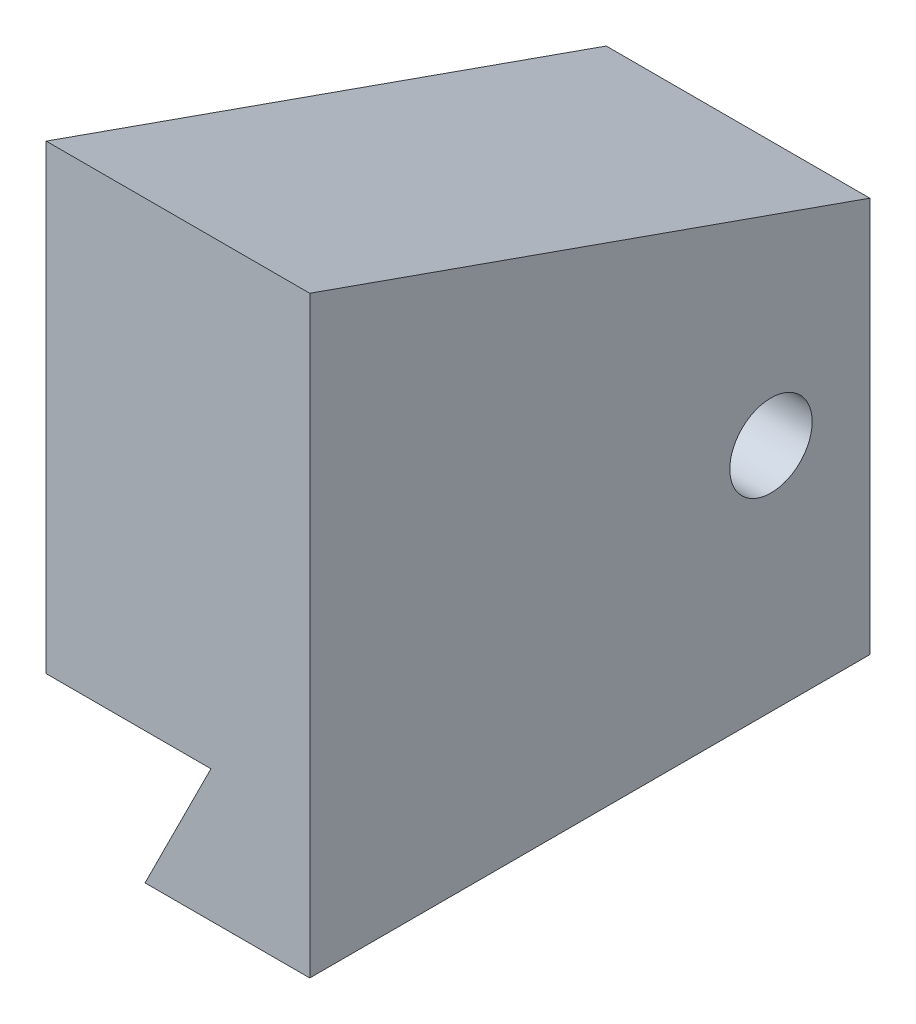
SolidWorks part; units mm, degrees
ref_plane "Front Plane" through (0, 0, 0) normal (0, 0, 1) x (1, 0, 0)
ref_plane "Top Plane" through (0, 0, 0) normal (0, 1, 0) x (1, 0, 0)
ref_plane "Right Plane" through (0, 0, 0) normal (1, 0, 0) x (0, 0, -1)
sketch "Sketch1" plane through (0, 0, 0) normal (1, 0, 0) x (0, 0, -1)
  line L0 (0, 0) -> (0, 12)
  line L1 (0, 12) -> (-17, 18)
  line L2 (-17, 18) -> (-17, 0)
  line L3 (-17, 0) -> (0, 0)
  dimension "D1" = 18
  dimension "D2" = 12
  dimension "D3" = 17
extrude "Boss-Extrude1" add sketch "Sketch1" along normal blind 8
sketch "Sketch2" plane through (8, 0, 0) normal (1, 0, 0) x (0, 0, -1)
  line L0 (-17, 18) -> (-17, 0) construction
  line L1 (-17, 5) -> (0, 5)
  line L2 (-17, 5) -> (-17, 0)
  line L3 (-17, 0) -> (0, 0)
  line L4 (0, 5) -> (0, 0)
  line L5 (0, 0) -> (0, 12) construction
  dimension "D1" = 5
extrude "Cut-Extrude1" [suppressed] cut sketch "Sketch2" against normal blind 4
sketch "Sketch3" plane through (0, 0, 0) normal (0, 0, -1) x (-1, 0, 0)
  line L0 (-8, 0) -> (-5, 0)
  line L1 (-8, 0) -> (0, 0) construction
  line L2 (-5, 0) -> (-3, 4)
  line L3 (-3, 4) -> (-8, 4)
  line L4 (-8, 0) -> (-8, 12) construction
  line L5 (-8, 4) -> (-8, 0)
  dimension "D1" = 5
  dimension "D2" = 3
  dimension "D3" = 4
extrude "Cut-Extrude2" cut sketch "Sketch3" against normal through all
sketch "Sketch5" plane through (8, 0, 0) normal (1, 0, 0) x (0, 0, -1)
  line L0 (0, 4) -> (0, 12) construction
  line L1 (-17, 4) -> (0, 4) construction
  circle A0 centre (-3, 7) radius 1
  dimension "D1" = 2
  dimension "D3" = 3
  dimension "D2" = 3
hole_wizard "M3x0.5 Tapped Hole1" positions "3DSketch1" profile "Sketch6" tap size "M3x0.5" standard "ANSI Metric" end condition through all
sketch3d "3DSketch1"
  point P0 (8, 7, 3)
sketch "Sketch6" plane through (8, 7, 3) normal (0, 1, 0) x (0, 0, -1)
  line L0 (0, 0) -> (0, 16)
  line L1 (0, 16) -> (1.25, 16)
  line L2 (1.25, 16) -> (1.25, 0)
  line L5 (1.25, 0) -> (0, 0)
  line L11 (0, -6.35) -> (0, 107.95) construction
  dimension "Thread Major Dia." = 2.5
  dimension "Thru Tap Drill Depth" = 16
mirror "Mirror1" about plane through (0, 0, 0) normal (1, 0, 0) of "M3x0.5 Tapped Hole1", "Cut-Extrude2", "Boss-Extrude1"
sketch "Sketch7" plane through (8, 0, 0) normal (1, 0, 0) x (0, 0, -1)
  line L1 (-18.597, 19.2943) -> (2.2281, 19.2943)
  line L2 (-18.597, 19.2943) -> (-18.597, -2.2409)
  line L3 (-18.597, -2.2409) -> (2.2281, -2.2409)
  line L4 (2.2281, 19.2943) -> (2.2281, -2.2409)
extrude "Cut-Extrude3" cut sketch "Sketch7" against normal blind 8
